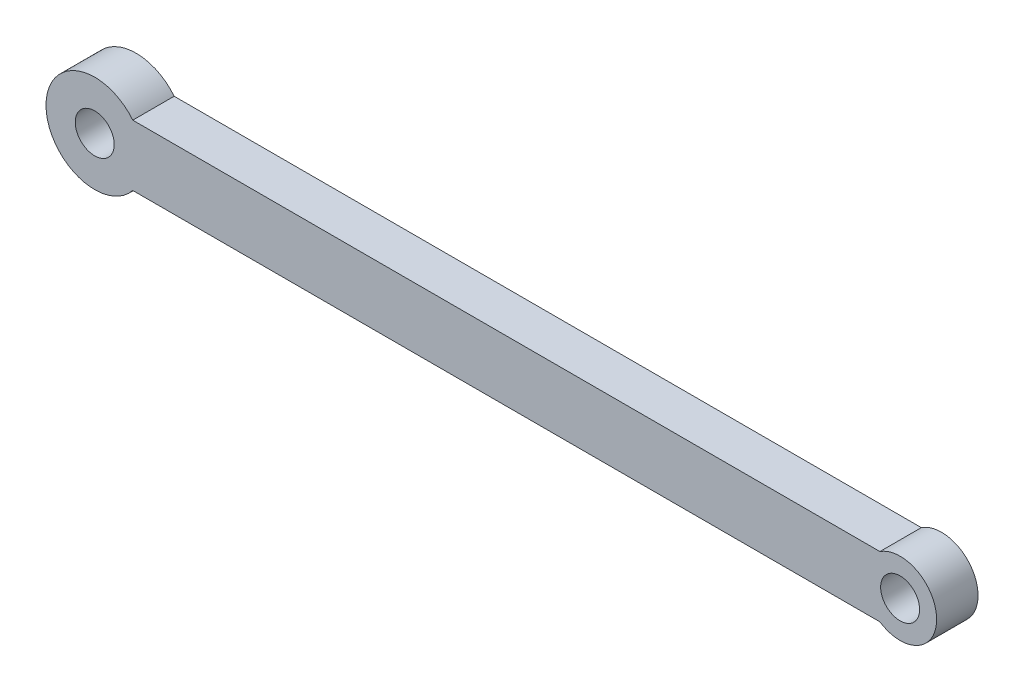
SolidWorks part; units mm, degrees
ref_plane "Plan de face" through (0, 0, 0) normal (0, 0, 1) x (1, 0, 0)
ref_plane "Plan de dessus" through (0, 0, 0) normal (0, 1, 0) x (1, 0, 0)
ref_plane "Plan de droite" through (0, 0, 0) normal (1, 0, 0) x (0, 0, -1)
sketch "Esquisse1" plane through (0, 0, 0) normal (0, 0, 1) x (1, 0, 0)
  line L0 (0, 0) -> (66.12, 0) construction
  line L1 (3.1225, 2.5) -> (64.4617, 2.5)
  line L2 (3.1225, -2.5) -> (64.4617, -2.5)
  circle A0 centre (0, 0) radius 4 construction
  circle A1 centre (66.12, 0) radius 3 construction
  arc A2 (3.1225, -2.5) -> (3.1225, 2.5) centre (0, 0) cw
  arc A3 (64.4617, 2.5) -> (64.4617, -2.5) centre (66.12, 0) cw
  circle A4 centre (0, 0) radius 1.6
  circle A5 centre (66.12, 0) radius 1.6
  dimension "D1" = 8
  dimension "D2" = 6
  dimension "D4" = 3.2
  dimension "D5" = 3.2
  dimension "D3" = 66.12
  dimension "D6" = 5
extrude "Boss.-Extru.1" add sketch "Esquisse1" along normal blind 3.4
